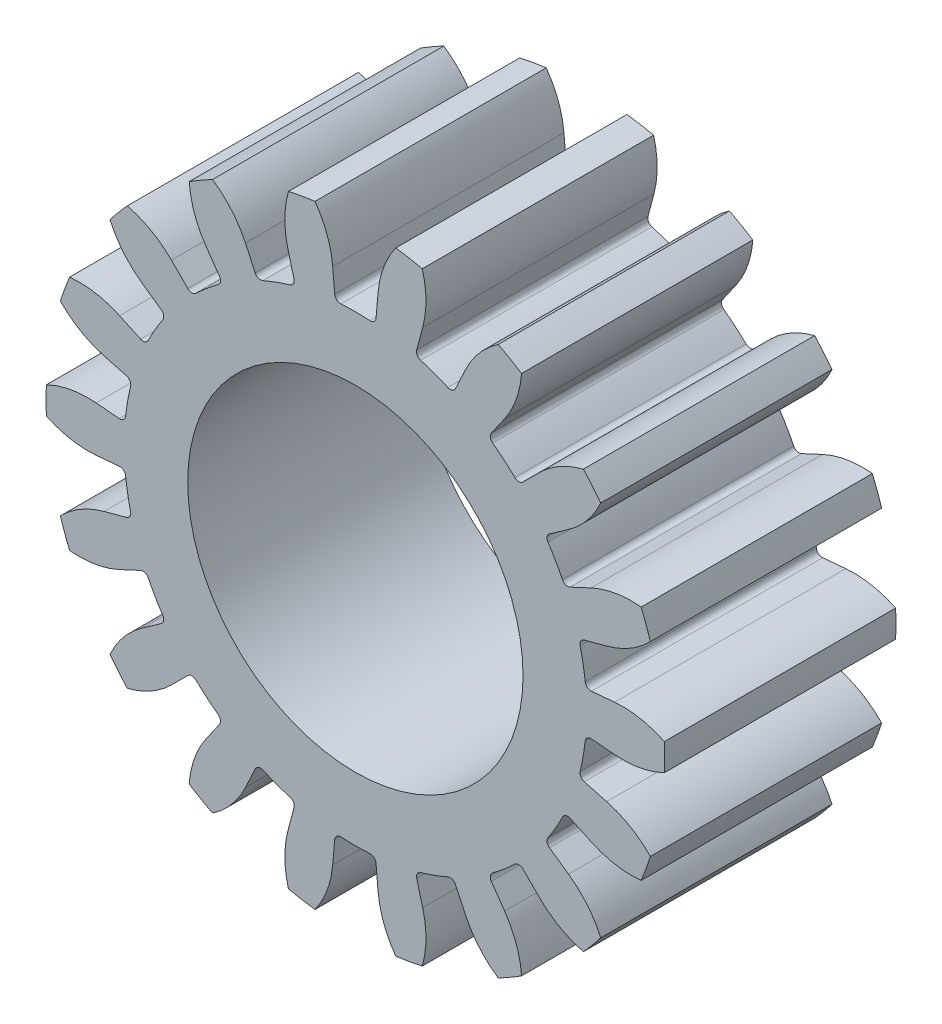
SolidWorks part; units mm, degrees
ref_plane "Front Plane" through (0, 0, 0) normal (0, 0, 1) x (1, 0, 0)
ref_plane "Top Plane" through (0, 0, 0) normal (0, 1, 0) x (1, 0, 0)
ref_plane "Right Plane" through (0, 0, 0) normal (1, 0, 0) x (0, 0, -1)
sketch "Sketch9" plane through (0, 0, 0) normal (0, 0, 1) x (1, 0, 0)
  line L0 (0, 0) -> (-7.5254, 0) construction
  line L5 (0, 0) -> (-5.8363, 0.5106) construction
  line L6 (0, 0) -> (-3.9392, 0.6946) construction
  line L7 (0, 0) -> (-5.6309, 0.2458) construction
  line L8 (-4.4829, 0.3922) -> (-3.9848, 0.3486)
  line L9 (-3.9392, 0.6946) -> (0, 0)
  line L10 (-3.9392, -0.6946) -> (0, 0)
  line L11 (-4.4829, -0.3922) -> (-3.9848, -0.3486)
  circle A0 centre (0, 0) radius 4.5 construction
  circle A1 centre (0, 0) radius 4 construction
  circle A2 centre (0, 0) radius 5.35 construction
  arc A3 (-4.4829, 0.3922) -> (-5.3449, 0.2334) centre (-4.6264, -1.2477) ccw
  circle A4 centre (0, 0) radius 2.85 construction
  arc A5 (-3.9848, 0.3486) -> (-3.9392, 0.6946) centre (0, 0) cw
  arc A6 (-5.3449, -0.2334) -> (-5.3449, 0.2334) centre (0, 0) cw
  arc A7 (-3.9848, -0.3486) -> (-3.9392, -0.6946) centre (0, 0) ccw
  arc A8 (-4.4829, -0.3922) -> (-5.3449, -0.2334) centre (-4.6264, 1.2477) cw
  dimension "D1" = 10.7
  dimension "D2" = 9
  dimension "D3" = 8
  dimension "D7" = 5.7
  dimension "D4" = 10
  dimension "D5" = 5
  dimension "D6" = 2.5
extrude "Boss-Extrude6" add sketch "Sketch9" along normal blind 4 contours A8 L11 A7 L10 L9 A5 L8 A3 A6
fillet "Fillet2" radius 0.1 2 edges at (-3.9848, 0.3486, 2) (-3.9848, -0.3486, 2)
pattern_circular "CirPattern5" count 18 over 360 about axis through (0, 0, 0) along (0, 0, 1) of "Boss-Extrude6", "Fillet2"
sketch "Sketch12" plane through (0, 0, 4) normal (0, 0, 1) x (1, 0, 0)
  circle A0 centre (0, 0) radius 2.9
  dimension "D1" = 5.8
extrude "Cut-Extrude2" cut sketch "Sketch12" against normal through all
